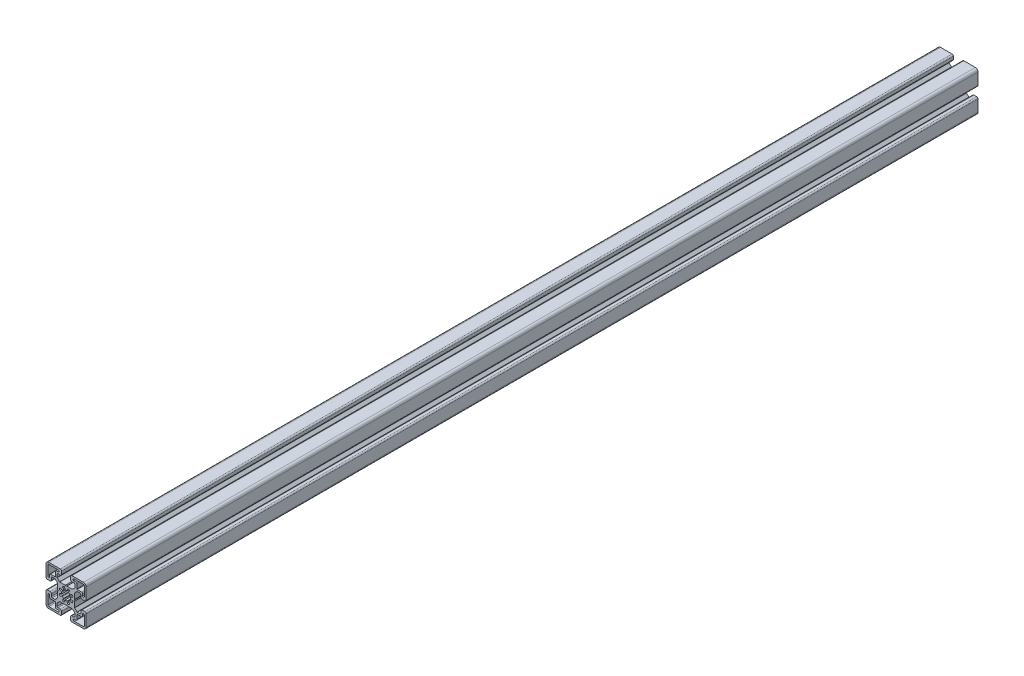
SolidWorks part; units mm, degrees
material "6061 Alloy"
ref_plane "Front Plane" through (0, 0, 0) normal (0, 0, 1) x (1, 0, 0)
ref_plane "Top Plane" through (0, 0, 0) normal (0, 1, 0) x (1, 0, 0)
ref_plane "Right Plane" through (0, 0, 0) normal (1, 0, 0) x (0, 0, -1)
sketch "Sketch1" plane through (0, 0, 0) normal (0, 0, 1) x (1, 0, 0)
  line L0 (-8.0293, -14.4831) -> (-6.0293, -14.4831)
  line L1 (-6.0293, -16.4831) -> (-16.5293, -16.4831)
  line L2 (-17.5293, -15.4831) -> (-17.5293, -4.9831)
  line L3 (-15.5293, -4.9831) -> (-15.5293, -6.9831)
  line L4 (-14.5293, -7.9831) -> (-9.4093, -7.9831)
  line L5 (-9.0293, -8.3631) -> (-9.0293, -13.4831)
  line L6 (-15.5293, 15.0169) -> (-15.5293, 13.0169)
  line L7 (-17.5293, 13.0169) -> (-17.5293, 23.5169)
  line L8 (-16.5293, 24.5169) -> (-6.0293, 24.5169)
  line L9 (-6.0293, 22.5169) -> (-8.0293, 22.5169)
  line L10 (-9.0293, 21.5169) -> (-9.0293, 16.3969)
  line L11 (-9.4093, 16.0169) -> (-14.5293, 16.0169)
  line L12 (14.9707, 16.3969) -> (14.9707, 21.5169)
  line L13 (13.9707, 22.5169) -> (11.9707, 22.5169)
  line L14 (11.9707, 24.5169) -> (22.4707, 24.5169)
  line L15 (23.4707, 23.5169) -> (23.4707, 13.0169)
  line L16 (21.4707, 13.0169) -> (21.4707, 15.0169)
  line L17 (20.4707, 16.0169) -> (15.3507, 16.0169)
  line L18 (8.8137, 0.2931) -> (7.1867, 1.3289)
  line L19 (5.6584, -0.1993) -> (6.6943, -1.826)
  line L20 (4.4692, -2.7478) -> (4.0512, -0.865)
  line L21 (1.8899, -0.8649) -> (1.4721, -2.7476)
  line L22 (-0.7531, -1.8261) -> (0.2827, -0.1991)
  line L23 (-1.2455, 1.3292) -> (-2.8722, 0.2933)
  line L24 (-3.794, 2.5184) -> (-1.9112, 2.9364)
  line L25 (-1.9111, 5.0977) -> (-3.7938, 5.5155)
  line L26 (-2.8723, 7.7407) -> (-1.2453, 6.7049)
  line L27 (0.283, 8.2331) -> (-0.7529, 9.8598)
  line L28 (1.4722, 10.7816) -> (1.8902, 8.8987)
  line L29 (4.0515, 8.8987) -> (4.4693, 10.7814)
  line L30 (6.6945, 9.8599) -> (5.6587, 8.2329)
  line L31 (7.1869, 6.7046) -> (8.8136, 7.7405)
  line L32 (9.7354, 5.5154) -> (7.8526, 5.0973)
  line L33 (7.8525, 2.936) -> (9.7352, 2.5183)
  line L34 (21.4707, -6.9831) -> (21.4707, -4.9831)
  line L35 (23.4707, -4.9831) -> (23.4707, -15.4831)
  line L36 (22.4707, -16.4831) -> (11.9707, -16.4831)
  line L37 (11.9707, -14.4831) -> (13.9707, -14.4831)
  line L38 (14.9707, -13.4831) -> (14.9707, -8.3631)
  line L39 (15.3507, -7.9831) -> (20.4707, -7.9831)
  line L40 (2.0707, -5.4831) -> (2.9707, -4.968)
  line L41 (2.9707, -4.968) -> (3.8707, -5.4831)
  line L42 (3.8707, -5.4831) -> (10.0223, -5.4831)
  line L43 (10.291, -5.5944) -> (12.9094, -8.2128)
  line L44 (13.0207, -8.4815) -> (13.0207, -11.4831)
  line L45 (12.0207, -12.4831) -> (9.5557, -12.4831)
  line L46 (8.0357, -14.0031) -> (8.0357, -16.9631)
  line L47 (9.5557, -18.4831) -> (22.4707, -18.4831)
  line L48 (25.4707, -15.4831) -> (25.4707, -2.5681)
  line L49 (23.9507, -1.0481) -> (20.9907, -1.0481)
  line L50 (19.4707, -2.5681) -> (19.4707, -5.0331)
  line L51 (18.4707, -6.0331) -> (15.4691, -6.0331)
  line L52 (15.2004, -5.9218) -> (12.582, -3.3034)
  line L53 (12.4707, -3.0347) -> (12.4707, 3.1169)
  line L54 (12.4707, 3.1169) -> (11.9511, 4.0169)
  line L55 (11.9511, 4.0169) -> (12.4707, 4.9169)
  line L56 (12.4707, 4.9169) -> (12.4707, 11.0685)
  line L57 (12.582, 11.3372) -> (15.2004, 13.9556)
  line L58 (15.4691, 14.0669) -> (18.4707, 14.0669)
  line L59 (19.4707, 13.0669) -> (19.4707, 10.6019)
  line L60 (20.9907, 9.0819) -> (23.9507, 9.0819)
  line L61 (25.4707, 10.6019) -> (25.4707, 23.5169)
  line L62 (22.4707, 26.5169) -> (9.5557, 26.5169)
  line L63 (8.0357, 24.9969) -> (8.0357, 22.0369)
  line L64 (9.5557, 20.5169) -> (12.0207, 20.5169)
  line L65 (13.0207, 19.5169) -> (13.0207, 16.5153)
  line L66 (12.9094, 16.2466) -> (10.291, 13.6282)
  line L67 (10.0223, 13.5169) -> (3.8707, 13.5169)
  line L68 (3.8707, 13.5169) -> (2.9707, 13.0017)
  line L69 (2.9707, 13.0017) -> (2.0707, 13.5169)
  line L70 (2.0707, 13.5169) -> (-4.0809, 13.5169)
  line L71 (-4.3496, 13.6282) -> (-6.968, 16.2466)
  line L72 (-7.0793, 16.5153) -> (-7.0793, 19.5169)
  line L73 (-6.0793, 20.5169) -> (-3.6143, 20.5169)
  line L74 (-2.0943, 22.0369) -> (-2.0943, 24.9969)
  line L75 (-3.6143, 26.5169) -> (-16.5293, 26.5169)
  line L76 (-19.5293, 23.5169) -> (-19.5293, 10.6019)
  line L77 (-18.0093, 9.0819) -> (-15.0493, 9.0819)
  line L78 (-13.5293, 10.6019) -> (-13.5293, 13.0669)
  line L79 (-12.5293, 14.0669) -> (-9.5277, 14.0669)
  line L80 (-9.259, 13.9556) -> (-6.6406, 11.3372)
  line L81 (-6.5293, 11.0685) -> (-6.5293, 4.9169)
  line L82 (-6.5293, 4.9169) -> (-6.0097, 4.0169)
  line L83 (-6.0097, 4.0169) -> (-6.5293, 3.1169)
  line L84 (-6.5293, 3.1169) -> (-6.5293, -3.0347)
  line L85 (-6.6406, -3.3034) -> (-9.259, -5.9218)
  line L86 (-9.5277, -6.0331) -> (-12.5293, -6.0331)
  line L87 (-13.5293, -5.0331) -> (-13.5293, -2.5681)
  line L88 (-15.0493, -1.0481) -> (-18.0093, -1.0481)
  line L89 (-19.5293, -2.5681) -> (-19.5293, -15.4831)
  line L90 (-16.5293, -18.4831) -> (-3.6143, -18.4831)
  line L91 (-2.0943, -16.9631) -> (-2.0943, -14.0031)
  line L92 (-3.6143, -12.4831) -> (-6.0793, -12.4831)
  line L93 (-7.0793, -11.4831) -> (-7.0793, -8.4815)
  line L94 (-6.968, -8.2128) -> (-4.3496, -5.5944)
  line L95 (-4.0809, -5.4831) -> (2.0707, -5.4831)
  arc A0 (-9.0293, -13.4831) -> (-8.0293, -14.4831) centre (-8.0293, -13.4831) ccw
  arc A1 (-6.0293, -16.4831) -> (-6.0293, -14.4831) centre (-6.0293, -15.4831) ccw
  arc A2 (-17.5293, -15.4831) -> (-16.5293, -16.4831) centre (-16.5293, -15.4831) ccw
  arc A3 (-15.5293, -4.9831) -> (-17.5293, -4.9831) centre (-16.5293, -4.9831) ccw
  arc A4 (-15.5293, -6.9831) -> (-14.5293, -7.9831) centre (-14.5293, -6.9831) ccw
  arc A5 (-9.0293, -8.3631) -> (-9.4093, -7.9831) centre (-9.4093, -8.3631) ccw
  arc A6 (-14.5293, 16.0169) -> (-15.5293, 15.0169) centre (-14.5293, 15.0169) ccw
  arc A7 (-17.5293, 13.0169) -> (-15.5293, 13.0169) centre (-16.5293, 13.0169) ccw
  arc A8 (-16.5293, 24.5169) -> (-17.5293, 23.5169) centre (-16.5293, 23.5169) ccw
  arc A9 (-6.0293, 22.5169) -> (-6.0293, 24.5169) centre (-6.0293, 23.5169) ccw
  arc A10 (-8.0293, 22.5169) -> (-9.0293, 21.5169) centre (-8.0293, 21.5169) ccw
  arc A11 (-9.4093, 16.0169) -> (-9.0293, 16.3969) centre (-9.4093, 16.3969) ccw
  arc A12 (14.9707, 16.3969) -> (15.3507, 16.0169) centre (15.3507, 16.3969) ccw
  arc A13 (14.9707, 21.5169) -> (13.9707, 22.5169) centre (13.9707, 21.5169) ccw
  arc A14 (11.9707, 24.5169) -> (11.9707, 22.5169) centre (11.9707, 23.5169) ccw
  arc A15 (23.4707, 23.5169) -> (22.4707, 24.5169) centre (22.4707, 23.5169) ccw
  arc A16 (21.4707, 13.0169) -> (23.4707, 13.0169) centre (22.4707, 13.0169) ccw
  arc A17 (21.4707, 15.0169) -> (20.4707, 16.0169) centre (20.4707, 15.0169) ccw
  arc A18 (10.2621, 0.7252) -> (10.454, 1.1885) centre (2.9707, 4.0169) ccw
  arc A19 (8.8137, 0.2931) -> (10.2621, 0.7252) centre (9.3507, 1.1367) ccw
  arc A20 (5.6584, -0.1993) -> (7.1867, 1.3289) centre (2.9707, 4.0169) ccw
  arc A21 (6.2622, -3.2746) -> (6.6943, -1.826) centre (5.8508, -2.3632) ccw
  arc A22 (5.799, -3.4665) -> (6.2622, -3.2746) centre (2.9707, 4.0169) ccw
  arc A23 (4.4692, -2.7478) -> (5.799, -3.4665) centre (5.4454, -2.5311) ccw
  arc A24 (1.8899, -0.8649) -> (4.0512, -0.865) centre (2.9707, 4.0169) ccw
  arc A25 (0.1423, -3.4664) -> (1.4721, -2.7476) centre (0.4958, -2.531) ccw
  arc A26 (-0.321, -3.2745) -> (0.1423, -3.4664) centre (2.9707, 4.0169) ccw
  arc A27 (-0.7531, -1.8261) -> (-0.321, -3.2745) centre (0.0905, -2.3631) ccw
  arc A28 (-1.2455, 1.3292) -> (0.2827, -0.1991) centre (2.9707, 4.0169) ccw
  arc A29 (-4.3208, 0.7254) -> (-2.8722, 0.2933) centre (-3.4094, 1.1368) ccw
  arc A30 (-4.5127, 1.1886) -> (-4.3208, 0.7254) centre (2.9707, 4.0169) ccw
  arc A31 (-3.794, 2.5184) -> (-4.5127, 1.1886) centre (-3.5773, 1.5422) ccw
  arc A32 (-1.9111, 5.0977) -> (-1.9112, 2.9364) centre (2.9707, 4.0169) ccw
  arc A33 (-4.5126, 6.8453) -> (-3.7938, 5.5155) centre (-3.5772, 6.4917) ccw
  arc A34 (-4.3207, 7.3085) -> (-4.5126, 6.8453) centre (2.9707, 4.0169) ccw
  arc A35 (-2.8723, 7.7407) -> (-4.3207, 7.3085) centre (-3.4093, 6.8971) ccw
  arc A36 (0.283, 8.2331) -> (-1.2453, 6.7049) centre (2.9707, 4.0169) ccw
  arc A37 (-0.3208, 11.3084) -> (-0.7529, 9.8598) centre (0.0906, 10.3969) ccw
  arc A38 (0.1424, 11.5003) -> (-0.3208, 11.3084) centre (2.9707, 4.0169) ccw
  arc A39 (1.4722, 10.7816) -> (0.1424, 11.5003) centre (0.496, 10.5648) ccw
  arc A40 (4.0515, 8.8987) -> (1.8902, 8.8987) centre (2.9707, 4.0169) ccw
  arc A41 (5.7991, 11.5002) -> (4.4693, 10.7814) centre (5.4456, 10.5648) ccw
  arc A42 (6.2624, 11.3083) -> (5.7991, 11.5002) centre (2.9707, 4.0169) ccw
  arc A43 (6.6945, 9.8599) -> (6.2624, 11.3083) centre (5.8509, 10.3969) ccw
  arc A44 (7.1869, 6.7046) -> (5.6587, 8.2329) centre (2.9707, 4.0169) ccw
  arc A45 (10.2622, 7.3084) -> (8.8136, 7.7405) centre (9.3508, 6.897) ccw
  arc A46 (10.4541, 6.8451) -> (10.2622, 7.3084) centre (2.9707, 4.0169) ccw
  arc A47 (9.7354, 5.5154) -> (10.4541, 6.8451) centre (9.5187, 6.4916) ccw
  arc A48 (7.8525, 2.936) -> (7.8526, 5.0973) centre (2.9707, 4.0169) ccw
  arc A49 (10.454, 1.1885) -> (9.7352, 2.5183) centre (9.5186, 1.542) ccw
  arc A50 (20.4707, -7.9831) -> (21.4707, -6.9831) centre (20.4707, -6.9831) ccw
  arc A51 (23.4707, -4.9831) -> (21.4707, -4.9831) centre (22.4707, -4.9831) ccw
  arc A52 (22.4707, -16.4831) -> (23.4707, -15.4831) centre (22.4707, -15.4831) ccw
  arc A53 (11.9707, -14.4831) -> (11.9707, -16.4831) centre (11.9707, -15.4831) ccw
  arc A54 (13.9707, -14.4831) -> (14.9707, -13.4831) centre (13.9707, -13.4831) ccw
  arc A55 (15.3507, -7.9831) -> (14.9707, -8.3631) centre (15.3507, -8.3631) ccw
  arc A56 (10.291, -5.5944) -> (10.0223, -5.4831) centre (10.0223, -5.8631) ccw
  arc A57 (13.0207, -8.4815) -> (12.9094, -8.2128) centre (12.6407, -8.4815) ccw
  arc A58 (12.0207, -12.4831) -> (13.0207, -11.4831) centre (12.0207, -11.4831) ccw
  arc A59 (9.5557, -12.4831) -> (8.0357, -14.0031) centre (9.5557, -14.0031) ccw
  arc A60 (8.0357, -16.9631) -> (9.5557, -18.4831) centre (9.5557, -16.9631) ccw
  arc A61 (22.4707, -18.4831) -> (25.4707, -15.4831) centre (22.4707, -15.4831) ccw
  arc A62 (25.4707, -2.5681) -> (23.9507, -1.0481) centre (23.9507, -2.5681) ccw
  arc A63 (20.9907, -1.0481) -> (19.4707, -2.5681) centre (20.9907, -2.5681) ccw
  arc A64 (18.4707, -6.0331) -> (19.4707, -5.0331) centre (18.4707, -5.0331) ccw
  arc A65 (15.2004, -5.9218) -> (15.4691, -6.0331) centre (15.4691, -5.6531) ccw
  arc A66 (12.4707, -3.0347) -> (12.582, -3.3034) centre (12.8507, -3.0347) ccw
  arc A67 (12.582, 11.3372) -> (12.4707, 11.0685) centre (12.8507, 11.0685) ccw
  arc A68 (15.4691, 14.0669) -> (15.2004, 13.9556) centre (15.4691, 13.6869) ccw
  arc A69 (19.4707, 13.0669) -> (18.4707, 14.0669) centre (18.4707, 13.0669) ccw
  arc A70 (19.4707, 10.6019) -> (20.9907, 9.0819) centre (20.9907, 10.6019) ccw
  arc A71 (23.9507, 9.0819) -> (25.4707, 10.6019) centre (23.9507, 10.6019) ccw
  arc A72 (25.4707, 23.5169) -> (22.4707, 26.5169) centre (22.4707, 23.5169) ccw
  arc A73 (9.5557, 26.5169) -> (8.0357, 24.9969) centre (9.5557, 24.9969) ccw
  arc A74 (8.0357, 22.0369) -> (9.5557, 20.5169) centre (9.5557, 22.0369) ccw
  arc A75 (13.0207, 19.5169) -> (12.0207, 20.5169) centre (12.0207, 19.5169) ccw
  arc A76 (12.9094, 16.2466) -> (13.0207, 16.5153) centre (12.6407, 16.5153) ccw
  arc A77 (10.0223, 13.5169) -> (10.291, 13.6282) centre (10.0223, 13.8969) ccw
  arc A78 (-4.3496, 13.6282) -> (-4.0809, 13.5169) centre (-4.0809, 13.8969) ccw
  arc A79 (-7.0793, 16.5153) -> (-6.968, 16.2466) centre (-6.6993, 16.5153) ccw
  arc A80 (-6.0793, 20.5169) -> (-7.0793, 19.5169) centre (-6.0793, 19.5169) ccw
  arc A81 (-3.6143, 20.5169) -> (-2.0943, 22.0369) centre (-3.6143, 22.0369) ccw
  arc A82 (-2.0943, 24.9969) -> (-3.6143, 26.5169) centre (-3.6143, 24.9969) ccw
  arc A83 (-16.5293, 26.5169) -> (-19.5293, 23.5169) centre (-16.5293, 23.5169) ccw
  arc A84 (-19.5293, 10.6019) -> (-18.0093, 9.0819) centre (-18.0093, 10.6019) ccw
  arc A85 (-15.0493, 9.0819) -> (-13.5293, 10.6019) centre (-15.0493, 10.6019) ccw
  arc A86 (-12.5293, 14.0669) -> (-13.5293, 13.0669) centre (-12.5293, 13.0669) ccw
  arc A87 (-9.259, 13.9556) -> (-9.5277, 14.0669) centre (-9.5277, 13.6869) ccw
  arc A88 (-6.5293, 11.0685) -> (-6.6406, 11.3372) centre (-6.9093, 11.0685) ccw
  arc A89 (-6.6406, -3.3034) -> (-6.5293, -3.0347) centre (-6.9093, -3.0347) ccw
  arc A90 (-9.5277, -6.0331) -> (-9.259, -5.9218) centre (-9.5277, -5.6531) ccw
  arc A91 (-13.5293, -5.0331) -> (-12.5293, -6.0331) centre (-12.5293, -5.0331) ccw
  arc A92 (-13.5293, -2.5681) -> (-15.0493, -1.0481) centre (-15.0493, -2.5681) ccw
  arc A93 (-18.0093, -1.0481) -> (-19.5293, -2.5681) centre (-18.0093, -2.5681) ccw
  arc A94 (-19.5293, -15.4831) -> (-16.5293, -18.4831) centre (-16.5293, -15.4831) ccw
  arc A95 (-3.6143, -18.4831) -> (-2.0943, -16.9631) centre (-3.6143, -16.9631) ccw
  arc A96 (-2.0943, -14.0031) -> (-3.6143, -12.4831) centre (-3.6143, -14.0031) ccw
  arc A97 (-7.0793, -11.4831) -> (-6.0793, -12.4831) centre (-6.0793, -11.4831) ccw
  arc A98 (-6.968, -8.2128) -> (-7.0793, -8.4815) centre (-6.6993, -8.4815) ccw
  arc A99 (-4.0809, -5.4831) -> (-4.3496, -5.5944) centre (-4.0809, -5.8631) ccw
extrude "Extrude1" add sketch "Sketch1" along normal blind 1000
